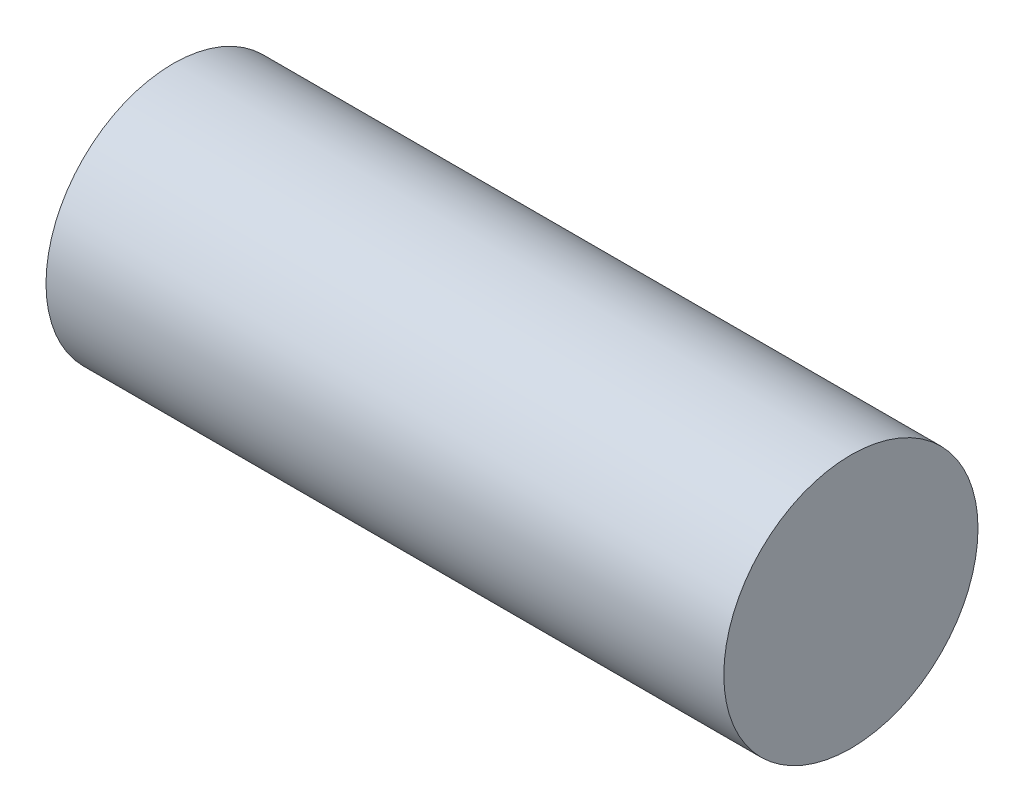
SolidWorks part; units mm, degrees
ref_plane "Front Plane" through (0, 0, 0) normal (0, 0, 1) x (1, 0, 0)
ref_plane "Top Plane" through (0, 0, 0) normal (0, 1, 0) x (1, 0, 0)
ref_plane "Right Plane" through (0, 0, 0) normal (1, 0, 0) x (0, 0, -1)
sketch "Sketch1" plane through (0, 0, 0) normal (1, 0, 0) x (0, 0, -1)
  circle A0 centre (0, 0) radius 0.75
  dimension "D1" = 1.5
extrude "Boss-Extrude1" add sketch "Sketch1" along normal blind 4
